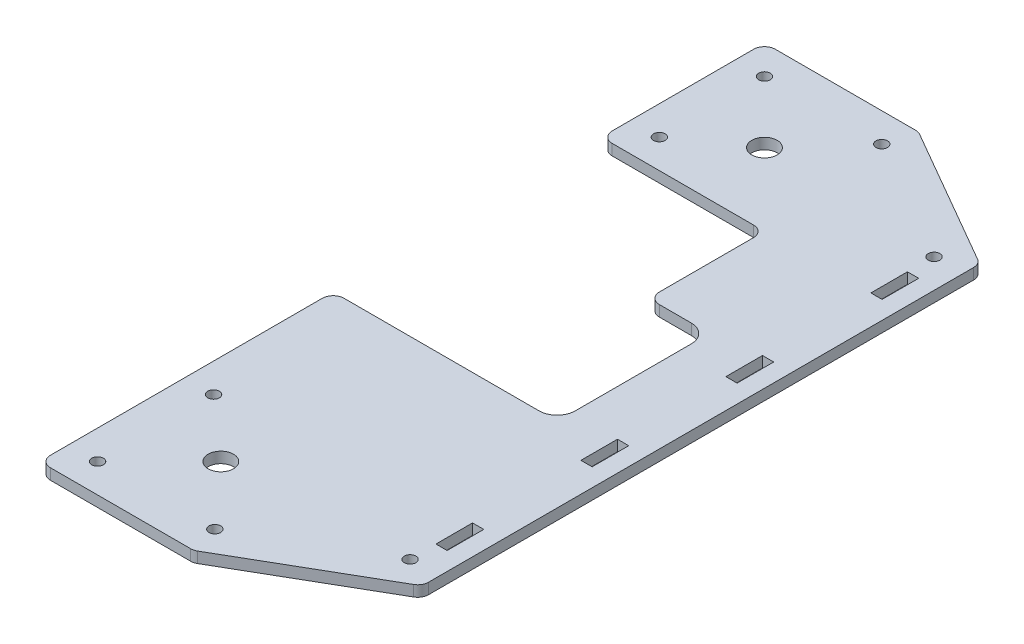
SolidWorks part; units mm, degrees
ref_plane "Front Plane" through (0, 0, 0) normal (0, 0, 1) x (1, 0, 0)
ref_plane "Top Plane" through (0, 0, 0) normal (0, 1, 0) x (1, 0, 0)
ref_plane "Right Plane" through (0, 0, 0) normal (1, 0, 0) x (0, 0, -1)
sketch "Sketch1" plane through (0, 0, 0) normal (0, 1, 0) x (1, 0, 0)
  line L0 (-85, 100) -> (85, 100) construction
  line L1 (-125, 100) -> (125, 100) construction
  line L2 (-125, 100) -> (-125, -100) construction
  line L3 (-125, -100) -> (125, -100) construction
  line L4 (125, 100) -> (125, -100) construction
  line L5 (85, 100) -> (125, 76.906) construction
  line L6 (125, 76.906) -> (125, -76.906) construction
  line L8 (-125, -76.906) -> (-125, 76.906) construction
  line L9 (-125, 76.906) -> (-85, 100) construction
  line L10 (-125, 0) -> (125, 0) construction
  line L11 (85, -100) -> (125, -76.906) construction
  line L12 (-85, -100) -> (85, -100) construction
  line L13 (-125, -76.906) -> (-85, -100) construction
  line L15 (-42.5, 100) -> (42.5, 100) construction
  line L16 (-42.5, 100) -> (-42.5, 65) construction
  line L17 (-42.5, 65) -> (42.5, 65) construction
  line L18 (42.5, 100) -> (42.5, 65) construction
  line L19 (42.5, -100) -> (42.5, -65) construction
  line L20 (-42.5, -65) -> (42.5, -65) construction
  line L21 (-42.5, -100) -> (-42.5, -65) construction
  line L22 (-42.5, -100) -> (42.5, -100) construction
  line L23 (42.5, 100) -> (85, 100)
  line L24 (85, 100) -> (125, 76.906)
  line L25 (125, 76.906) -> (125, -76.906)
  line L26 (125, -76.906) -> (85, -100)
  line L27 (85, -100) -> (42.5, -100)
  line L28 (42.5, 100) -> (42.5, -100)
  line L29 (99.3, 22) -> (67.3, 22) construction
  line L30 (103.3, -14) -> (103.3, 18) construction
  line L31 (63.3, 18) -> (63.3, -14) construction
  line L32 (67.3, -18) -> (99.3, -18) construction
  line L33 (99.3, 22) -> (67.3, 22) construction
  line L34 (103.3, -14) -> (103.3, 18) construction
  line L35 (63.3, 18) -> (63.3, -14) construction
  line L36 (67.3, -18) -> (99.3, -18) construction
  line L37 (99.3, 23) -> (67.3, 23)
  line L38 (62.3, 18) -> (62.3, -14)
  line L39 (67.3, -19) -> (99.3, -19)
  line L40 (104.3, -14) -> (104.3, 18)
  arc A0 (67.3, 22) -> (63.3, 18) centre (67.3, 18) ccw construction
  arc A1 (103.3, 18) -> (99.3, 22) centre (99.3, 18) ccw construction
  arc A2 (63.3, -14) -> (67.3, -18) centre (67.3, -14) ccw construction
  arc A3 (99.3, -18) -> (103.3, -14) centre (99.3, -14) ccw construction
  arc A4 (103.3, 18) -> (99.3, 22) centre (99.3, 18) ccw construction
  arc A5 (67.3, 22) -> (63.3, 18) centre (67.3, 18) ccw construction
  arc A6 (63.3, -14) -> (67.3, -18) centre (67.3, -14) ccw construction
  arc A7 (99.3, -18) -> (103.3, -14) centre (99.3, -14) ccw construction
  arc A8 (104.3, 18) -> (99.3, 23) centre (99.3, 18) ccw
  arc A9 (67.3, 23) -> (62.3, 18) centre (67.3, 18) ccw
  arc A10 (62.3, -14) -> (67.3, -19) centre (67.3, -14) ccw
  arc A11 (99.3, -19) -> (104.3, -14) centre (99.3, -14) ccw
  point P4 (0, 100)
  point P6 (-125, 0)
  point P9 (0, 0)
  point P22 (0, 65)
  dimension "D1" = 250
  dimension "D2" = 200
  dimension "D3" = 60
  dimension "D4" = 60
  dimension "D5" = 40
  dimension "D6" = 85
  dimension "D7" = 35
  dimension "D8" = 1
extrude "Boss-Extrude1" add sketch "Sketch1" along normal blind 3
sketch "Sketch2" plane through (0, 3, 0) normal (0, 1, 0) x (1, 0, 0)
  line L0 (42.5, 100) -> (42.5, -100) construction
  line L1 (42.5, 55) -> (87.5, 55)
  line L2 (42.5, 55) -> (42.5, -19)
  line L3 (42.5, -19) -> (87.5, -19)
  line L4 (87.5, 55) -> (87.5, -19)
  line L5 (67.3, -19) -> (99.3, -19) construction
  dimension "D1" = 74
  dimension "D2" = 45
extrude "Cut-Extrude1" cut sketch "Sketch2" against normal up to next
fillet "Fillet2" radius 3 10 edges at (42.5, 1.5, 19) (42.5, 1.5, 100) (85, 1.5, 100) (125, 1.5, 76.906) (125, 1.5, -76.906) (85, 1.5, -100) (42.5, 1.5, -100) (87.5, 1.5, -55) (42.5, 1.5, -55) (87.5, 1.5, -23)
sketch "Sketch3" plane through (0, 3, 0) normal (0, 1, 0) x (1, 0, 0)
  line L0 (118.45, 14.95) -> (118.45, -14.95) construction
  line L5 (116.9, 14.95) -> (120, 14.95)
  line L6 (116.9, 14.95) -> (116.9, 25.05)
  line L7 (116.9, 25.05) -> (120, 25.05)
  line L8 (120, 14.95) -> (120, 25.05)
  line L9 (116.9, -14.95) -> (120, -14.95)
  line L10 (116.9, -14.95) -> (116.9, -25.05)
  line L11 (116.9, -25.05) -> (120, -25.05)
  line L12 (120, -14.95) -> (120, -25.05)
  line L13 (125, -75.1739) -> (125, 75.1739) construction
  line L14 (116.9, 65.05) -> (120, 65.05)
  line L15 (116.9, 65.05) -> (116.9, 54.95)
  line L16 (116.9, 54.95) -> (120, 54.95)
  line L17 (120, 65.05) -> (120, 54.95)
  line L18 (116.9, -54.95) -> (120, -54.95)
  line L19 (116.9, -54.95) -> (116.9, -65.05)
  line L20 (116.9, -65.05) -> (120, -65.05)
  line L21 (120, -54.95) -> (120, -65.05)
  point P0 (120, 20)
  point P1 (120, -20)
  point P21 (120, 60)
  point P22 (120, -60)
  point P25 (118.45, 0)
  dimension "D1" = 40
  dimension "D2" = 40
  dimension "D3" = 3.1
  dimension "D4" = 10.1
  dimension "D5" = 5
  dimension "D6" = 40
extrude "Cut-Extrude2" cut sketch "Sketch3" against normal through all
sketch "Sketch4" plane through (0, 3, 0) normal (0, 1, 0) x (1, 0, 0)
  line L0 (84.1962, 100) -> (45.5, 100) construction
  line L1 (42.5, 97) -> (42.5, 58) construction
  line L2 (84.5, 55) -> (45.5, 55) construction
  line L4 (42.5, -22) -> (42.5, -97) construction
  line L5 (45.5, -100) -> (84.1962, -100) construction
  line L6 (125, -75.1739) -> (125, 75.1739) construction
  line L7 (123.5, 77.772) -> (85.6962, 99.5981) construction
  line L8 (85.6962, -99.5981) -> (123.5, -77.772) construction
  circle A0 centre (50.5, 92) radius 1.6
  circle A1 centre (50.5, 63) radius 1.6
  circle A2 centre (50.5, -60) radius 1.6
  circle A3 centre (50.5, -92) radius 1.6
  circle A4 centre (117, 72.2872) radius 1.6
  circle A5 centre (117, -72.2872) radius 1.6
  circle A6 centre (82.8564, 92) radius 1.6
  circle A7 centre (82.8564, -92) radius 1.6
  dimension "D1" = 3.2
  dimension "D2" = 8
  dimension "D3" = 8
  dimension "D4" = 8
  dimension "D5" = 8
  dimension "D6" = 8
  dimension "D7" = 40
  dimension "D8" = 8
  dimension "D9" = 8
  dimension "D10" = 8
  dimension "D11" = 8
  dimension "D12" = 8
  dimension "D13" = 8
  dimension "D14" = 8
  dimension "D15" = 8
  dimension "D16" = 8
  dimension "D17" = 8
extrude "Cut-Extrude3" cut sketch "Sketch4" against normal up to next
sketch "Sketch5" plane through (0, 3, 0) normal (0, 1, 0) x (1, 0, 0)
  line L0 (0, 0) -> (125, 0) construction
  line L1 (125, -75.1739) -> (125, 75.1739) construction
  line L2 (42.5, 97) -> (42.5, 58) construction
  line L3 (84.1962, 100) -> (45.5, 100) construction
  circle A0 centre (67.5, 75) radius 3.5
  circle A2 centre (67.5, -75) radius 3.5
  dimension "D1" = 7
  dimension "D2" = 25
  dimension "D3" = 25
extrude "Cut-Extrude4" cut sketch "Sketch5" against normal through all
